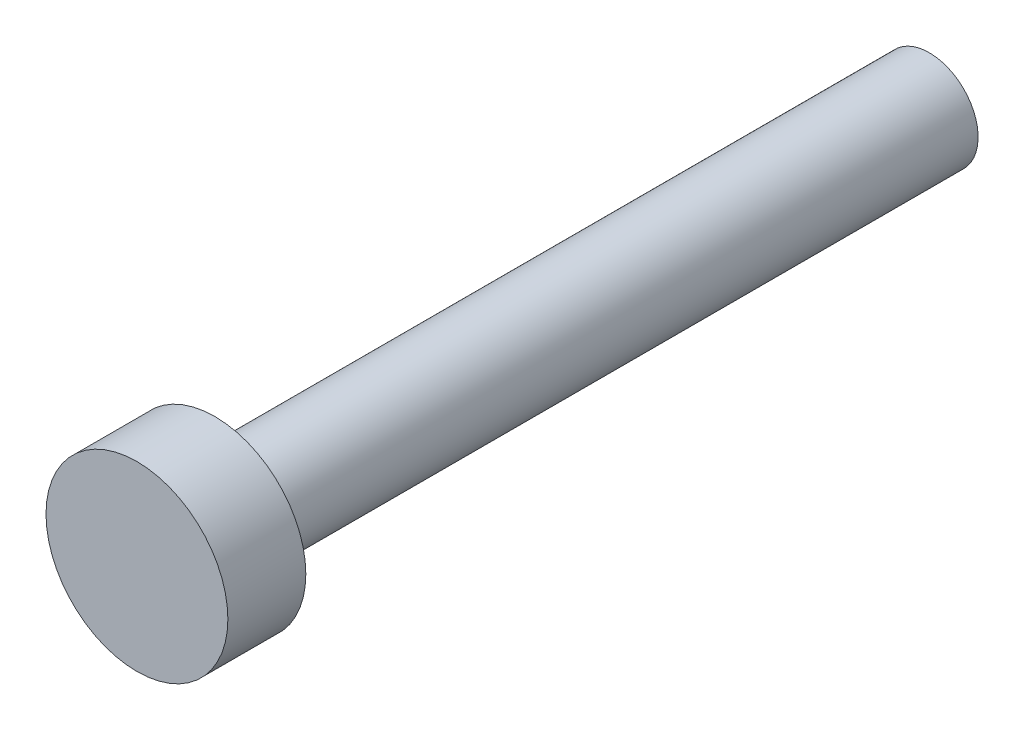
SolidWorks part; units mm, degrees
ref_plane "Plan de face" through (0, 0, 0) normal (0, 0, 1) x (1, 0, 0)
ref_plane "Plan de dessus" through (0, 0, 0) normal (0, 1, 0) x (1, 0, 0)
ref_plane "Plan de droite" through (0, 0, 0) normal (1, 0, 0) x (0, 0, -1)
sketch "Esquisse1" plane through (0, 0, 0) normal (0, 0, 1) x (1, 0, 0)
  circle A0 centre (0, 0) radius 2.8
  dimension "D1" = 5.6
extrude "Boss.-Extru.1" add sketch "Esquisse1" along normal blind 2.4
sketch "Esquisse2" plane through (0, 0, 0) normal (0, 0, -1) x (-1, 0, 0)
  circle A0 centre (0, 0) radius 1.5
  dimension "D1" = 3
extrude "Boss.-Extru.2" add sketch "Esquisse2" along normal blind 22
